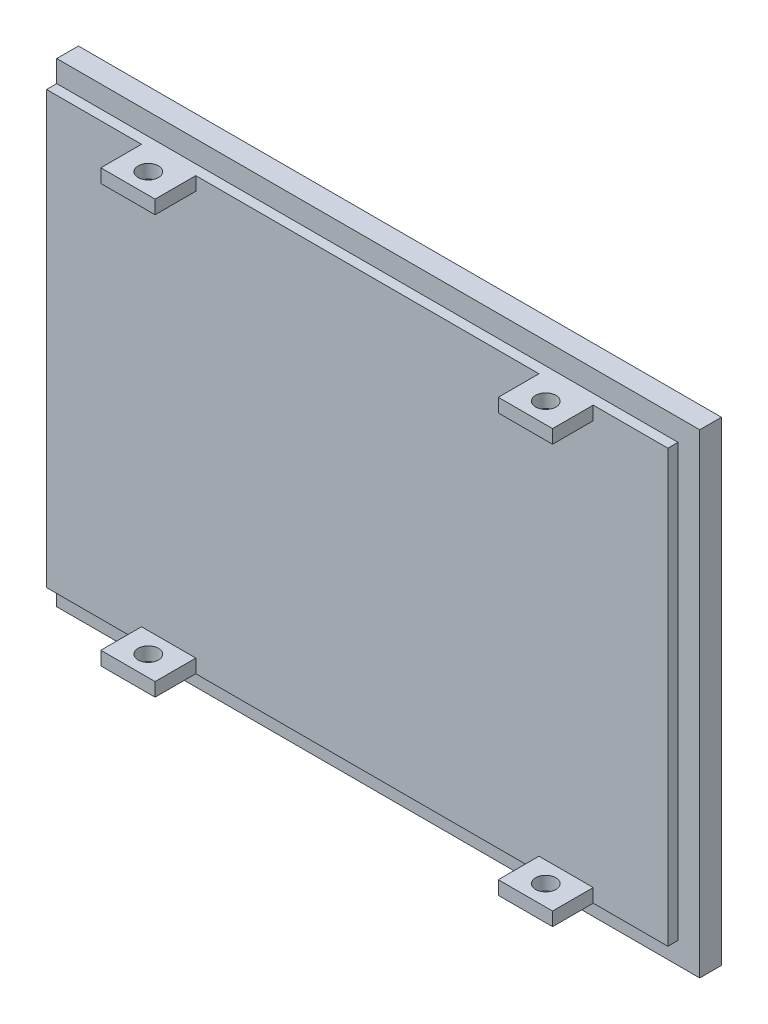
SolidWorks part; units mm, degrees
ref_plane "前视基准面" through (0, 0, 0) normal (0, 0, 1) x (1, 0, 0)
ref_plane "上视基准面" through (0, 0, 0) normal (0, 1, 0) x (1, 0, 0)
ref_plane "右视基准面" through (0, 0, 0) normal (1, 0, 0) x (0, 0, -1)
other "Configuration Table"
sketch "草图1" plane through (0, 0, 0) normal (0, 0, 1) x (1, 0, 0)
  line L1 (-47.3, 35) -> (47.5, 35)
  line L2 (-47.3, 35) -> (-47.3, -35)
  line L3 (-47.3, -35) -> (47.5, -35)
  line L4 (47.5, 35) -> (47.5, -35)
  line L5 (-47.3, 35) -> (47.5, -35) construction
  line L6 (-47.3, -35) -> (47.5, 35) construction
  point P0 (0.1, 0)
  dimension "D1" = 70
  dimension "D2" = 94.8
extrude "凸台-拉伸1" add sketch "草图1" along normal blind 3.2
sketch "草图3" plane through (0, 0, 3.2) normal (0, 0, 1) x (1, 0, 0)
  line L1 (44.3, -31.8) -> (-44.3, -31.8)
  line L2 (44.3, -31.8) -> (44.3, 31.8)
  line L3 (44.3, 31.8) -> (-44.3, 31.8)
  line L4 (-44.3, -31.8) -> (-44.3, 31.8)
  line L5 (44.3, -31.8) -> (-44.3, 31.8) construction
  line L6 (44.3, 31.8) -> (-44.3, -31.8) construction
  point P0 (0, 0)
  dimension "D1" = 63.6
  dimension "D2" = 88.6
extrude "凸台-拉伸2" add sketch "草图3" along normal blind 1.5
sketch "草图4" plane through (0, 0, 4.7) normal (0, 0, 1) x (1, 0, 0)
  line L0 (0, 31.8) -> (0, -31.8) construction
  line L1 (44.3, 31.8) -> (-44.3, 31.8) construction
  line L2 (-44.3, -31.8) -> (44.3, -31.8) construction
  line L3 (-44.3, 0) -> (44.3, 0) construction
  line L4 (-44.3, 31.8) -> (-44.3, -31.8) construction
  line L5 (44.3, -31.8) -> (44.3, 31.8) construction
  line L7 (33.3, 29.8) -> (25.3, 29.8)
  line L8 (33.3, 29.8) -> (33.3, 31.8)
  line L9 (33.3, 31.8) -> (25.3, 31.8)
  line L10 (25.3, 29.8) -> (25.3, 31.8)
  line L11 (33.3, 29.8) -> (25.3, 31.8) construction
  line L12 (33.3, 31.8) -> (25.3, 29.8) construction
  line L13 (33.3, -29.8) -> (33.3, -31.8)
  line L14 (33.3, -29.8) -> (25.3, -29.8)
  line L15 (25.3, -29.8) -> (25.3, -31.8)
  line L16 (33.3, -31.8) -> (25.3, -31.8)
  line L17 (33.3, -29.8) -> (25.3, -31.8) construction
  line L18 (-33.3, -29.8) -> (-25.3, -31.8) construction
  line L19 (-33.3, 31.8) -> (-25.3, 29.8) construction
  line L20 (-33.3, 29.8) -> (-25.3, 31.8) construction
  line L21 (-33.3, -31.8) -> (-25.3, -31.8)
  line L22 (-25.3, -29.8) -> (-25.3, -31.8)
  line L23 (-33.3, -29.8) -> (-25.3, -29.8)
  line L24 (-33.3, -29.8) -> (-33.3, -31.8)
  line L25 (-25.3, 29.8) -> (-25.3, 31.8)
  line L26 (-33.3, 31.8) -> (-25.3, 31.8)
  line L27 (-33.3, 29.8) -> (-25.3, 29.8)
  line L28 (-33.3, 29.8) -> (-33.3, 31.8)
  point P12 (29.3, 30.8)
  point P29 (-29.3, 30.8)
  dimension "D1" = 8
  dimension "D2" = 2
  dimension "D3" = 1
  dimension "D4" = 15
extrude "凸台-拉伸3" add sketch "草图4" along normal blind 6
sketch "草图5" plane through (0, 31.8, 0) normal (0, 1, 0) x (1, 0, 0)
  line L0 (44.3, -3.2) -> (-44.3, -3.2) construction
  circle A0 centre (29.3, -7.7) radius 1.5
  circle A1 centre (-29.3, -7.7) radius 1.5
  dimension "D1" = 4.5
  dimension "D2" = 3
  dimension "D3" = 4.5
  dimension "D5" = 15
  dimension "D6" = 15
extrude "切除-拉伸1" cut sketch "草图5" against normal blind 100
sketch "草图6" plane through (0, 0, 3.2) normal (0, 0, 1) x (1, 0, 0)
  line L0 (-44.3, 31.8) -> (-44.3, -31.8)
  line L1 (-44.3, -31.8) -> (-47.3, -31.8)
  line L2 (-47.3, 35) -> (-47.3, -35) construction
  line L3 (-47.3, -31.8) -> (-47.3, 31.8)
  line L4 (-47.3, 31.8) -> (-44.3, 31.8)
extrude "凸台-拉伸4" add sketch "草图6" along normal blind 1.5
